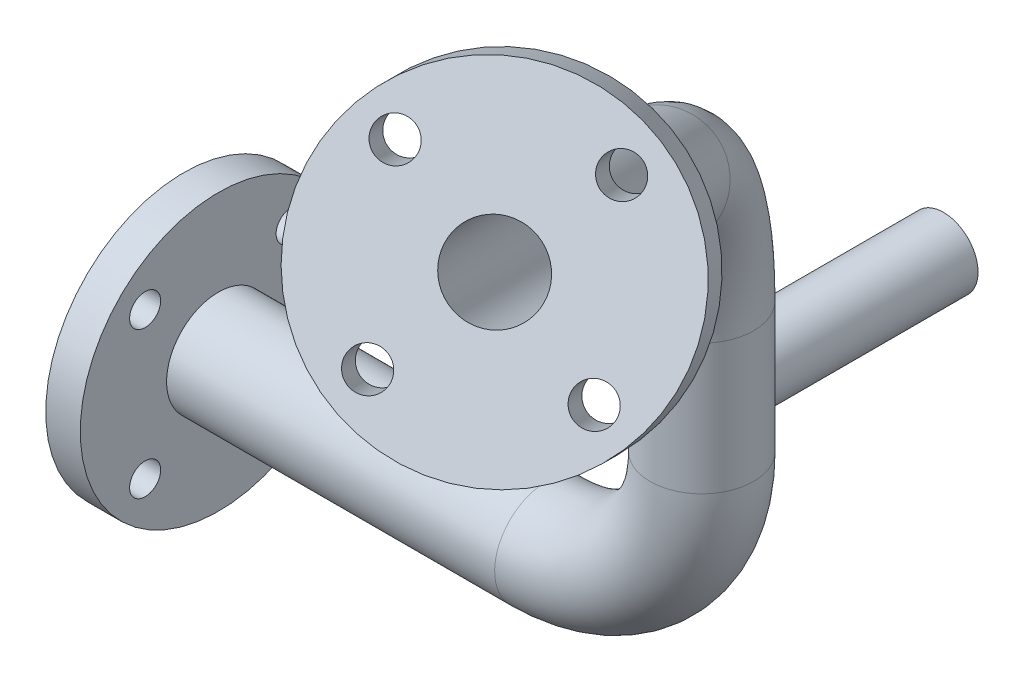
SolidWorks part; units mm, degrees
ref_plane "前视基准面" through (0, 0, 0) normal (0, 0, 1) x (1, 0, 0)
ref_plane "上视基准面" through (0, 0, 0) normal (0, 1, 0) x (1, 0, 0)
ref_plane "右视基准面" through (0, 0, 0) normal (1, 0, 0) x (0, 0, -1)
sketch3d "3D草图1"
  line L0 (0, 0, 0) -> (105, 0, 0)
  line L1 (150, 45, 0) -> (150, 82.7896, 0)
  line L2 (166.538, 136.538, 28.9414) -> (230, 200, 140)
  arc A0 (105, 0, 0) -> (150, 45, 0) centre (105, 45, 0) ccw
  arc A1 (150, 82.7896, 0) -> (166.538, 136.538, 28.9414) centre (179.7683, 82.7896, 52.0946) ccw
  point P6 (150, 0, 0)
  point P7 (105, 45, 45)
  point P10 (150, 120, 0)
  point P11 (231.8629, 82.7896, 22.3263)
  dimension "D1" = 45
  dimension "D2" = 60
sweep "扫描2" add path "3D草图1" circular profile diameter 30 parameters "D3"=30
sketch "草图2" plane through (0, 0, 0) normal (1, 0, 0) x (0, 0, -1)
  circle A0 centre (0, 0) radius 40
extrude "凸台-拉伸1" add sketch "草图2" along normal blind 10
sketch3d "3D草图2"
  line L0 (230, 200, 140) -> (224.6667, 194.6667, 130.6667)
sweep "扫描4" add path "3D草图2" circular profile diameter 90 parameters "D3"=90
sketch3d "3D草图3"
  line L0 (150, 60, -5) -> (150, 60, -70)
sweep "扫描6" add path "3D草图3" circular profile diameter 20 parameters "D3"=20
sketch3d "3D草图4"
  line L0 (-5, 0, 0) -> (105, 0, 0)
  line L1 (150, 45, 0) -> (150, 82.7896, 0)
  line L2 (166.538, 136.538, 28.9414) -> (232.2222, 202.2222, 143.8889)
  arc A0 (105, 0, 0) -> (150, 45, 0) centre (105, 45, 0) ccw
  arc A1 (150, 82.7896, 0) -> (166.538, 136.538, 28.9414) centre (179.7683, 82.7896, 52.0946) ccw
  point P6 (150, 0, 0)
  point P7 (105, 45, 45)
  point P10 (150, 120, 0)
  point P11 (231.8629, 82.7896, 22.3263)
  dimension "D1" = 45
  dimension "D2" = 60
sweep "切除-扫描2" cut path "3D草图4" circular profile diameter 24 parameters "D3"=24
sketch "草图7" plane through (0, 0, 0) normal (1, 0, 0) x (0, 0, -1)
  circle A0 centre (-21.2132, 21.2132) radius 4.5
  circle A1 centre (21.2132, 21.2132) radius 4.5
  circle A2 centre (21.2132, -21.2132) radius 4.5
  circle A3 centre (-21.2132, -21.2132) radius 4.5
extrude "切除-拉伸1" cut sketch "草图7" along normal blind 10
sketch3d "3D草图10"
  line L0 (196.7139, 214.4249, 130.2055) -> (205.6028, 223.3138, 145.7611)
sweep "切除-扫描14" cut path "3D草图10" circular profile diameter 11 parameters "D3"=11
sketch3d "3D草图11"
  line L0 (238.4619, 214.4249, 106.3505) -> (247.3508, 223.3138, 121.9061)
sweep "切除-扫描16" cut path "3D草图11" circular profile diameter 11 parameters "D3"=11
sketch3d "3D草图12"
  line L0 (207.3159, 171.3529, 148.7605) -> (216.2048, 180.2418, 164.3161)
sweep "切除-扫描18" cut path "3D草图12" circular profile diameter 11 parameters "D3"=11
sketch3d "3D草图13"
  line L0 (249.0639, 171.3529, 124.9055) -> (257.9528, 180.2418, 140.4611)
sweep "切除-扫描20" cut path "3D草图13" circular profile diameter 11 parameters "D3"=11
sketch3d "3D草图15"
  line L0 (150, 60, 10) -> (150, 60, -70)
sweep "切除-扫描24" cut path "3D草图15" circular profile diameter 14 parameters "D3"=14
